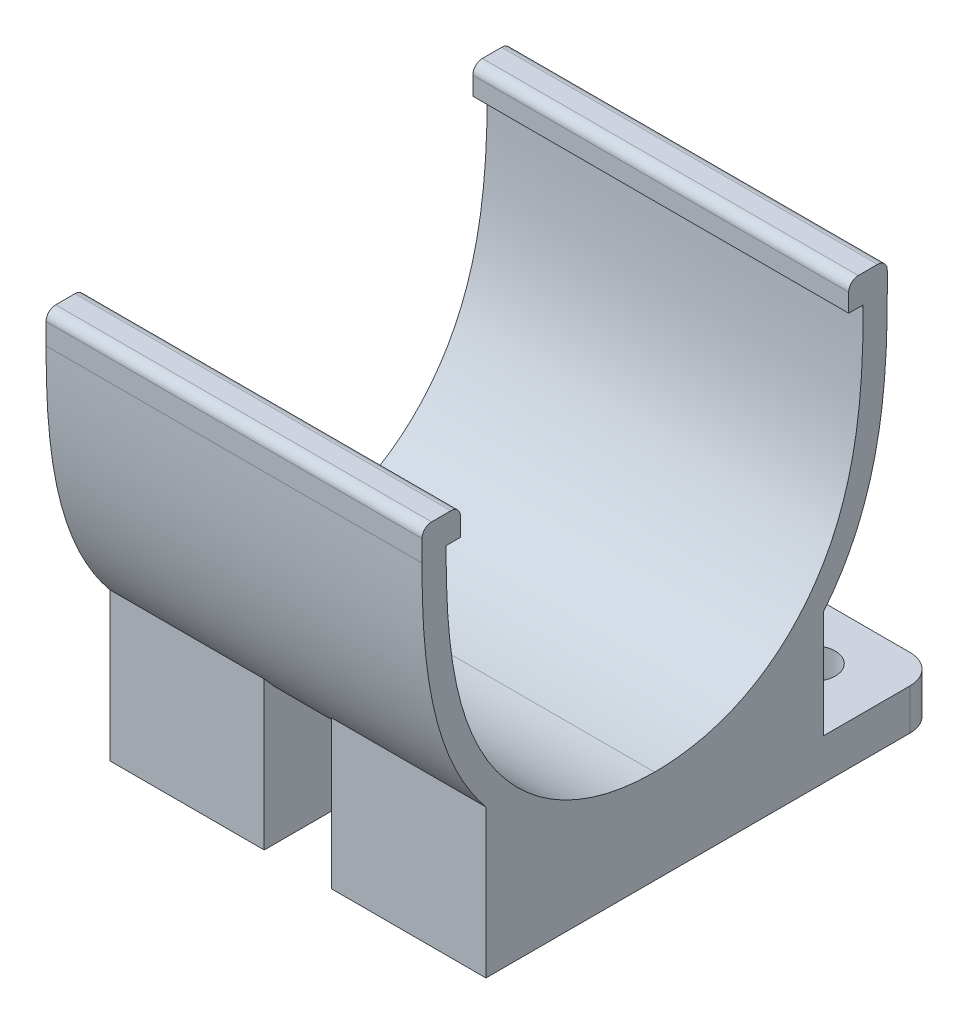
SolidWorks part; units mm, degrees
ref_plane "Front Plane" through (0, 0, 0) normal (0, 0, 1) x (1, 0, 0)
ref_plane "Top Plane" through (0, 0, 0) normal (0, 1, 0) x (1, 0, 0)
ref_plane "Right Plane" through (0, 0, 0) normal (1, 0, 0) x (0, 0, -1)
sketch "Sketch1" plane through (0, 0, 0) normal (1, 0, 0) x (0, 0, -1)
  line L0 (-21.635, -1.19) -> (-24.135, -1.19) construction
  line L1 (21.635, -1.19) -> (24.135, -1.19) construction
  line L2 (24.135, -1.19) -> (24.135, 2)
  line L3 (24.135, 2) -> (20.135, 2)
  line L4 (20.135, 2) -> (20.135, -0.89)
  line L5 (20.135, -0.89) -> (21.635, -0.89)
  line L6 (21.635, -0.89) -> (21.635, -1.19)
  line L7 (0, 0) -> (0, 5.8411) construction
  line L8 (-20.135, -0.89) -> (-21.635, -0.89)
  line L9 (-21.635, -0.89) -> (-21.635, -1.19)
  line L10 (-20.135, 2) -> (-20.135, -0.89)
  line L11 (-24.135, 2) -> (-20.135, 2)
  line L12 (-24.135, -1.19) -> (-24.135, 2)
  line L13 (19.735, -0.89) -> (20.135, -0.89) construction
  line L14 (19.735, -1.19) -> (19.735, 0) construction
  line L15 (20.135, -1.19) -> (20.135, -0.89) construction
  line L16 (21.135, -1.19) -> (-21.135, -1.19) construction
  line L17 (19.735, 0) -> (-19.735, 0) construction
  spline S0 degree 3 poles (626.557, 2889.1566) (292.2526, -13.5422) (-286.4957, -150.1813) (203.3883, 246.8462) (-1880.2927, -2355.5498) knots -4.329418 -4.329418 -4.329418 -4.329418 0.532714 5.637063 5.637063 5.637063 5.637063 only from (0, -31.55) to (-21.135, -1.19)
  spline S1 degree 3 poles (0, -31.55) (-8.9089, -31.55) (-20.4011, -21.9995) (-21.135, -7.0764) (-21.135, -1.19) knots 0 0 0 0 0.532714 1 1 1 1 construction
  spline S2 degree 3 poles (1880.2857, -2355.541) (-203.3877, 246.8457) (286.4945, -150.1806) (-292.2506, -13.5427) (-626.5534, 2889.1255) knots -4.637057 -4.637057 -4.637057 -4.637057 0.467286 5.3294 5.3294 5.3294 5.3294 only from (21.135, -1.19) to (0, -31.55)
  spline S3 degree 3 poles (21.135, -1.19) (21.135, -7.0764) (20.4011, -21.9995) (8.9089, -31.55) (0, -31.55) knots 0 0 0 0 0.467286 1 1 1 1 construction
  spline S4 degree 1 poles (21.635, -1.19) (0, -32.05) knots 0 0 1 1 construction
  spline S5 degree 1 poles (0, -32.05) (-21.635, -1.19) knots 0 0 1 1 construction
  spline S6 degree 3 poles (21.635, -1.19) (21.635, -1.9985) (21.6227, -3.592) (21.5101, -6.9652) (21.1304, -11.3011) (20.0604, -16.4841) (18.1161, -21.3821) (15.1187, -25.7076) (11.7777, -28.5934) (8.6068, -30.3241) (5.9868, -31.2963) (3.6015, -31.8051) (1.5867, -32.0142) (0.5246, -32.05) (0, -32.05) knots 0 0 0 0 0.0625 0.125 0.25 0.375 0.5 0.625 0.75 0.8125 0.875 0.9375 0.96875 1 1 1 1
  spline S7 degree 3 poles (0, -32.05) (-0.5246, -32.05) (-1.5867, -32.0142) (-3.6015, -31.8051) (-5.9868, -31.2963) (-8.6068, -30.3241) (-11.7777, -28.5934) (-15.1187, -25.7076) (-18.1161, -21.3821) (-20.0604, -16.4841) (-21.1304, -11.3011) (-21.5101, -6.9652) (-21.6227, -3.592) (-21.635, -1.9985) (-21.635, -1.19) knots 0 0 0 0 0.03125 0.0625 0.125 0.1875 0.25 0.375 0.5 0.625 0.75 0.875 0.9375 1 1 1 1
  spline S8 degree 1 poles (24.135, -1.19) (0, -34.55) knots 0 0 1 1 construction
  spline S9 degree 1 poles (0, -34.55) (-24.135, -1.19) knots 0 0 1 1 construction
  spline S10 degree 3 poles (24.135, -1.19) (24.135, -1.5974) (24.1319, -2.404) (24.108, -4.0826) (24.0356, -6.2451) (23.849, -8.9257) (23.4222, -12.5687) (22.4768, -17.1742) (20.3439, -22.5637) (17.0067, -27.3875) (13.2374, -30.6472) (9.6449, -32.608) (6.6822, -33.7068) (4.0029, -34.2776) (1.7556, -34.5105) (0.5813, -34.55) (0, -34.55) knots 0 0 0 0 0.03125 0.0625 0.125 0.1875 0.25 0.375 0.5 0.625 0.75 0.8125 0.875 0.9375 0.96875 1 1 1 1
  spline S11 degree 3 poles (0, -34.55) (-0.5813, -34.55) (-1.7556, -34.5105) (-4.0029, -34.2776) (-6.6822, -33.7068) (-9.6449, -32.608) (-13.2374, -30.6472) (-17.0067, -27.3875) (-20.3439, -22.5637) (-22.4768, -17.1742) (-23.4222, -12.5687) (-23.849, -8.9257) (-24.0356, -6.2451) (-24.108, -4.0826) (-24.1319, -2.404) (-24.135, -1.5974) (-24.135, -1.19) knots 0 0 0 0 0.03125 0.0625 0.125 0.1875 0.25 0.375 0.5 0.625 0.75 0.8125 0.875 0.9375 0.96875 1 1 1 1
  dimension "D3" = 0.4
  dimension "D4" = 0.3
  dimension "D5" = 2
  dimension "D1" = 0.5
  dimension "D2" = 3
extrude "Boss-Extrude1" add sketch "Sketch1" along normal mid plane 39
sketch "Sketch2" plane through (0, 0, 0) normal (0, 1, 0) x (1, 0, 0)
  line L0 (34.5, 161) -> (64.5, 131)
  line L1 (34.5, 131) -> (64.5, 161)
sketch "Sketch4" plane through (19.5, 0, 0) normal (1, 0, 0) x (0, 0, -1)
  line L0 (-17.5, -26.4315) -> (-17.5, -42.55)
  line L1 (-17.5, -42.55) -> (17.5, -42.55)
  line L2 (17.5, -42.55) -> (17.5, -26.4315)
  line L3 (0, 0) -> (0, -42.55) construction
  spline S0 degree 3 poles (-108.9539, 1996.8843) (-17.9629, 18.1788) (-24.452, 20.131) (-24.108, -4.0826) (-24.0356, -6.2451) (-23.849, -8.9257) (-23.4222, -12.5687) (-22.4768, -17.1742) (-20.3439, -22.5637) (-17.0067, -27.3875) (-13.2374, -30.6472) (-9.6449, -32.608) (-6.6822, -33.7068) (-4.0029, -34.2776) (25.1625, -37.2994) (84.7325, 7.6887) (-1990.086, 160.1545) knots -1.678133 -1.678133 -1.678133 -1.678133 0.03125 0.0625 0.125 0.1875 0.25 0.375 0.5 0.625 0.75 0.8125 0.875 0.9375 0.96875 2.497229 2.497229 2.497229 2.497229 only from (-24.135, -1.19) to (0, -34.55) construction
  spline S1 degree 3 poles (1990.0533, 160.1521) (-84.7319, 7.6882) (-25.1624, -37.2994) (4.0029, -34.2776) (6.6822, -33.7068) (9.6449, -32.608) (13.2374, -30.6472) (17.0067, -27.3875) (20.3439, -22.5637) (22.4768, -17.1742) (23.4222, -12.5687) (23.849, -8.9257) (24.0356, -6.2451) (24.108, -4.0826) (24.452, 20.1311) (17.9628, 18.1788) (108.9558, 1996.9257) knots -1.497221 -1.497221 -1.497221 -1.497221 0.03125 0.0625 0.125 0.1875 0.25 0.375 0.5 0.625 0.75 0.8125 0.875 0.9375 0.96875 2.678145 2.678145 2.678145 2.678145 only from (0, -34.55) to (24.135, -1.19) construction
  spline S2 degree 3 poles (-17.5, -26.4315) (-17.2761, -26.7042) (-15.7715, -28.4557) (-13.2374, -30.6472) (-9.6449, -32.608) (-6.6822, -33.7068) (-4.0029, -34.2776) (-1.7556, -34.5105) (-0.5813, -34.55) (0, -34.55) knots 0.602407 0.602407 0.602407 0.602407 0.625 0.75 0.8125 0.875 0.9375 0.96875 1 1 1 1
  spline S3 degree 3 poles (0, -34.55) (0.5813, -34.55) (1.7556, -34.5105) (4.0029, -34.2776) (6.6822, -33.7068) (9.6449, -32.608) (13.2374, -30.6472) (15.7715, -28.4557) (17.2761, -26.7042) (17.5, -26.4315) knots 0 0 0 0 0.03125 0.0625 0.125 0.1875 0.25 0.375 0.397593 0.397593 0.397593 0.397593
  dimension "D1" = 35
  dimension "D2" = 8
extrude "Boss-Extrude2" add sketch "Sketch4" against normal up to surface (39 mm away) up to face at (-19.5, -4.78, 0.1786)
sketch "Sketch5" plane through (0, -42.55, 0) normal (0, -1, 0) x (1, 0, 0)
  line L0 (0, 0) -> (55, 0) construction
  line L1 (55, 0) -> (55, -25) construction
  line L3 (40, -40) -> (70, -10)
  line L4 (70, -40) -> (40, -10)
  line L5 (34.5, -161) -> (64.5, -131) construction
  line L6 (34.5, -131) -> (64.5, -161) construction
  point P6 (55, -25)
  point P10 (55, -25)
  dimension "D1" = 25
  dimension "D2" = 55
  dimension "D3" = 45
sketch "Sketch11" plane through (0, -42.55, 0) normal (0, -1, 0) x (1, 0, 0)
  line L0 (33, -4) -> (19.5, 17.5)
  line L1 (33, -4) -> (47, -4)
  line L2 (33, -4) -> (33, -46) construction
  line L3 (33, -46) -> (47, -46)
  line L4 (47, -4) -> (47, -46)
  line L5 (19.5, 17.5) -> (19.5, -17.5)
  line L6 (19.5, -17.5) -> (33, -46)
  line L7 (33, -40) -> (47, -40) construction
  line L8 (33, -10) -> (47, -10) construction
  line L9 (55, -25) -> (47, -25) construction
  dimension "D1" = 14
  dimension "D2" = 42
extrude "Boss-Extrude4" [suppressed] add sketch "Sketch11" against normal blind 5
fillet "Fillet2" [suppressed] radius 7.25
hole_wizard "#8 Clearance Hole2" [suppressed] positions "Sketch12" profile "Sketch13" hole size "#8" standard "ANSI Inch"
sketch "Sketch12" [suppressed] plane through (0, -37.55, 0) normal (0, 1, 0) x (1, 0, 0)
  point P0 (40, 40)
  point P3 (40, 10)
sketch "Sketch13" plane through (40, -37.55, -40) normal (1, 0, 0) x (0, 0, 1)
  line L0 (0, 0) -> (0, 5)
  line L1 (0, 5) -> (2.2479, 5)
  line L2 (2.2479, 5) -> (2.2479, 0)
  line L5 (2.2479, 0) -> (0, 0)
  line L11 (0, -6.35) -> (0, 107.95) construction
  dimension "Thru Hole Dia." = 4.4958
  dimension "Thru Hole Depth" = 5
sketch "Sketch14" plane through (0, 0, 0) normal (1, 0, 0) x (0, 0, -1)
  line L0 (-17.5, -42.55) -> (-17.5, -26.4315)
  line L1 (-17.5, -42.55) -> (-17.5, -26.4315) construction
  line L2 (-17.5, -42.55) -> (17.5, -42.55)
  line L3 (17.5, -42.55) -> (17.5, -26.4315)
  line L4 (17.5, -26.4315) -> (17.5, -42.55) construction
  spline S0 degree 3 poles (108.9539, 1996.8843) (17.9629, 18.1788) (24.452, 20.131) (24.108, -4.0826) (24.0356, -6.2451) (23.849, -8.9257) (23.4222, -12.5687) (22.4768, -17.1742) (20.3439, -22.5637) (17.0067, -27.3875) (13.2374, -30.6472) (9.6449, -32.608) (6.6822, -33.7068) (4.0029, -34.2776) (-25.1625, -37.2994) (-84.7325, 7.6887) (1990.086, 160.1545) knots -1.678133 -1.678133 -1.678133 -1.678133 0.03125 0.0625 0.125 0.1875 0.25 0.375 0.5 0.625 0.75 0.8125 0.875 0.9375 0.96875 2.497229 2.497229 2.497229 2.497229 only from (24.135, -1.19) to (0, -34.55) construction
  spline S1 degree 3 poles (-1990.0533, 160.1521) (84.7319, 7.6882) (25.1624, -37.2994) (-4.0029, -34.2776) (-6.6822, -33.7068) (-9.6449, -32.608) (-13.2374, -30.6472) (-17.0067, -27.3875) (-20.3439, -22.5637) (-22.4768, -17.1742) (-23.4222, -12.5687) (-23.849, -8.9257) (-24.0356, -6.2451) (-24.108, -4.0826) (-24.452, 20.1311) (-17.9628, 18.1788) (-108.9558, 1996.9257) knots -1.497221 -1.497221 -1.497221 -1.497221 0.03125 0.0625 0.125 0.1875 0.25 0.375 0.5 0.625 0.75 0.8125 0.875 0.9375 0.96875 2.678145 2.678145 2.678145 2.678145 only from (0, -34.55) to (-24.135, -1.19) construction
  spline S2 degree 3 poles (17.5, -26.4315) (17.2761, -26.7042) (15.7715, -28.4557) (13.2374, -30.6472) (9.6449, -32.608) (6.6822, -33.7068) (4.0029, -34.2776) (1.7556, -34.5105) (0.5813, -34.55) (0, -34.55) knots 0.602407 0.602407 0.602407 0.602407 0.625 0.75 0.8125 0.875 0.9375 0.96875 1 1 1 1
  spline S3 degree 3 poles (0, -34.55) (-0.5813, -34.55) (-1.7556, -34.5105) (-4.0029, -34.2776) (-6.6822, -33.7068) (-9.6449, -32.608) (-13.2374, -30.6472) (-15.7715, -28.4557) (-17.2761, -26.7042) (-17.5, -26.4315) knots 0 0 0 0 0.03125 0.0625 0.125 0.1875 0.25 0.375 0.397593 0.397593 0.397593 0.397593
extrude "Cut-Extrude3" cut sketch "Sketch14" against normal mid plane 7
sketch "Sketch15" plane through (0, -42.55, 0) normal (0, -1, 0) x (1, 0, 0)
  line L0 (-19.5, 14.67) -> (-11.775, 14.67)
  line L1 (-19.5, -17.5) -> (-19.5, 17.5) construction
  line L2 (-11.775, 4.67) -> (-19.5, 4.67)
  line L3 (-19.5, 4.67) -> (-19.5, 14.67)
  circle A0 centre (-11.775, 9.67) radius 3.125 construction
  circle A1 centre (-11.775, 9.67) radius 3.125 construction
  arc A2 (-11.775, 14.67) -> (-11.775, 4.67) centre (-11.775, 9.67) cw
  dimension "D1" = 10
extrude "Cut-Extrude4" cut sketch "Sketch15" against normal through all
chamfer "Chamfer1" [suppressed] distance 3 angle 45
chamfer "Chamfer2" [suppressed] distance 0.75 angle 45
fillet "Fillet3" radius 1 4 edges at (0, 2, 24.135) (0, 2, 20.135) (0, 2, -20.135) (0, 2, -24.135)
sketch "Sketch16" plane through (0, -42.55, 0) normal (0, -1, 0) x (1, 0, 0)
  line L0 (-12.5, -23.5) -> (12.5, -23.5)
sketch "Sketch17" plane through (0, -42.55, 0) normal (0, -1, 0) x (1, 0, 0)
  line L0 (-12.5, -23.5) -> (12.5, -23.5) construction
  line L1 (-3.5, -17.5) -> (-19.5, -17.5)
  line L2 (-3.5, -17.5) -> (-3.5, -29.5)
  line L3 (-3.5, -29.5) -> (-19.5, -29.5)
  line L4 (-19.5, -17.5) -> (-19.5, -29.5)
  line L5 (3.5, -17.5) -> (19.5, -17.5)
  line L6 (3.5, -17.5) -> (3.5, -29.5)
  line L7 (3.5, -29.5) -> (19.5, -29.5)
  line L8 (19.5, -17.5) -> (19.5, -29.5)
  line L9 (-12.5, -23.5) -> (12.5, -23.5) construction
  line L10 (-3.5, -29.5) -> (3.5, -29.5) construction
  line L11 (0, -29.5) -> (0, -23.5) construction
  point P18 (3.5, -23.5)
  dimension "D1" = 12
extrude "Boss-Extrude5" add sketch "Sketch17" against normal blind 5
hole_wizard "#8 Clearance Hole3" positions "Sketch18" profile "Sketch19" hole size "#8" standard "ANSI Inch"
sketch "Sketch18" plane through (0, -37.55, 0) normal (0, 1, 0) x (1, 0, 0)
  point P0 (-12.5, 23.5)
  point P3 (12.5, 23.5)
sketch "Sketch19" plane through (-12.5, -37.55, -23.5) normal (1, 0, 0) x (0, 0, 1)
  line L0 (0, 0) -> (0, 5)
  line L1 (0, 5) -> (2.2479, 5)
  line L2 (2.2479, 5) -> (2.2479, 0)
  line L5 (2.2479, 0) -> (0, 0)
  line L11 (0, -6.35) -> (0, 107.95) construction
  dimension "Thru Hole Dia." = 4.4958
  dimension "Thru Hole Depth" = 5
fillet "Fillet4" radius 3 4 edges at (19.5, -40.05, -29.5) (3.5, -40.05, -29.5) (-3.5, -40.05, -29.5) (-19.5, -40.05, -29.5)
chamfer "Chamfer3" distance 0.75 angle 45 19 edges at (12.5, -42.55, -25.7479) (-12.5, -42.55, -25.7479) (11.5, -42.55, -29.5) (4.3787, -42.55, -28.6213) (18.6213, -42.55, -28.6213) (-11.5, -42.55, -29.5) (-19.5, -42.55, -10.915) (-18.6213, -42.55, -28.6213) (-4.3787, -42.55, -28.6213) (-11.5, -42.55, 17.5) (19.5, -42.55, -4.5) (11.5, -42.55, 17.5) (-3.5, -42.55, -4.5) (3.5, -42.55, -4.5) (-19.5, -42.55, 16.085) (-15.6375, -42.55, 4.67) (-6.775, -42.55, 9.67) (-15.6375, -42.55, 14.67)
